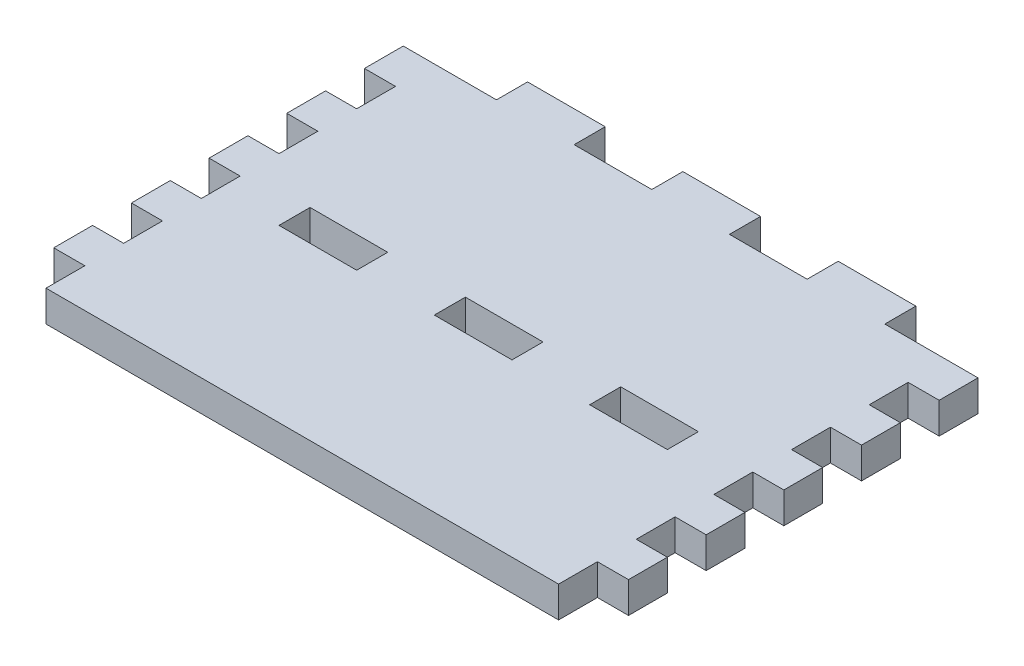
SolidWorks part; units mm, degrees
material "Maple"
ref_plane "Front Plane" through (0, 0, 0) normal (0, 0, 1) x (1, 0, 0)
ref_plane "Top Plane" through (0, 0, 0) normal (0, 1, 0) x (1, 0, 0)
ref_plane "Right Plane" through (0, 0, 0) normal (1, 0, 0) x (0, 0, -1)
sketch "Sketch1" plane through (0, 0, 0) normal (0, 1, 0) x (1, 0, 0)
  line L1 (0, 0) -> (66, 0)
  line L2 (0, 0) -> (0, -50)
  line L3 (0, -50) -> (66, -50)
  line L4 (66, 0) -> (66, -50)
  dimension "D1" = 66
  dimension "D2" = 50
extrude "Boss-Extrude1" add sketch "Sketch1" along normal blind 4
sketch "Sketch2" plane through (0, 4, 0) normal (0, 1, 0) x (1, 0, 0)
  line L10 (0, 0) -> (0, -50) construction
  line L11 (0, 0) -> (-4, 0)
  line L12 (0, 0) -> (0, -5)
  line L13 (0, -5) -> (-4, -5)
  line L14 (-4, 0) -> (-4, -5)
  line L15 (66, 0) -> (70, 0)
  line L16 (66, 0) -> (66, -5)
  line L17 (66, -5) -> (70, -5)
  line L18 (70, 0) -> (70, -5)
  dimension "D1" = 4
  dimension "D2" = 5
extrude "Boss-Extrude2" add sketch "Sketch2" against normal through all
pattern_linear "LPattern1" count 5 spacing 10 along (0, 0, 1) of "Boss-Extrude2"
sketch "Sketch3" plane through (0, 4, 0) normal (0, 1, 0) x (1, 0, 0)
  line L0 (33, -50) -> (33, 0) construction
  line L1 (0, -50) -> (66, -50) construction
  line L2 (70, 0) -> (-4, 0) construction
  line L4 (28, 0) -> (38, 0)
  line L5 (28, 0) -> (28, 4)
  line L6 (28, 4) -> (38, 4)
  line L7 (38, 0) -> (38, 4)
  line L8 (28, 0) -> (38, 4) construction
  line L9 (28, 4) -> (38, 0) construction
  point P6 (33, 2)
  point P11 (38.6193, 12.5315)
  dimension "D1" = 4
  dimension "D2" = 10
extrude "Boss-Extrude3" add sketch "Sketch3" against normal through all
pattern_linear "LPattern2" count 2 spacing 20 along (1, 0, 0) count 2 spacing 20 along (-1, 0, 0) of "Boss-Extrude3"
sketch "Sketch4" plane through (0, 0, 0) normal (0, -1, 0) x (1, 0, 0)
  line L1 (8, 24) -> (18, 24)
  line L2 (8, 24) -> (8, 28)
  line L3 (8, 28) -> (18, 28)
  line L4 (18, 24) -> (18, 28)
  line L5 (28, 24) -> (38, 24)
  line L6 (28, 24) -> (28, 28)
  line L7 (28, 28) -> (38, 28)
  line L8 (38, 24) -> (38, 28)
  line L9 (48, 24) -> (58, 24)
  line L10 (48, 24) -> (48, 28)
  line L11 (48, 28) -> (58, 28)
  line L12 (58, 24) -> (58, 28)
extrude "Cut-Extrude1" cut sketch "Sketch4" against normal through all
